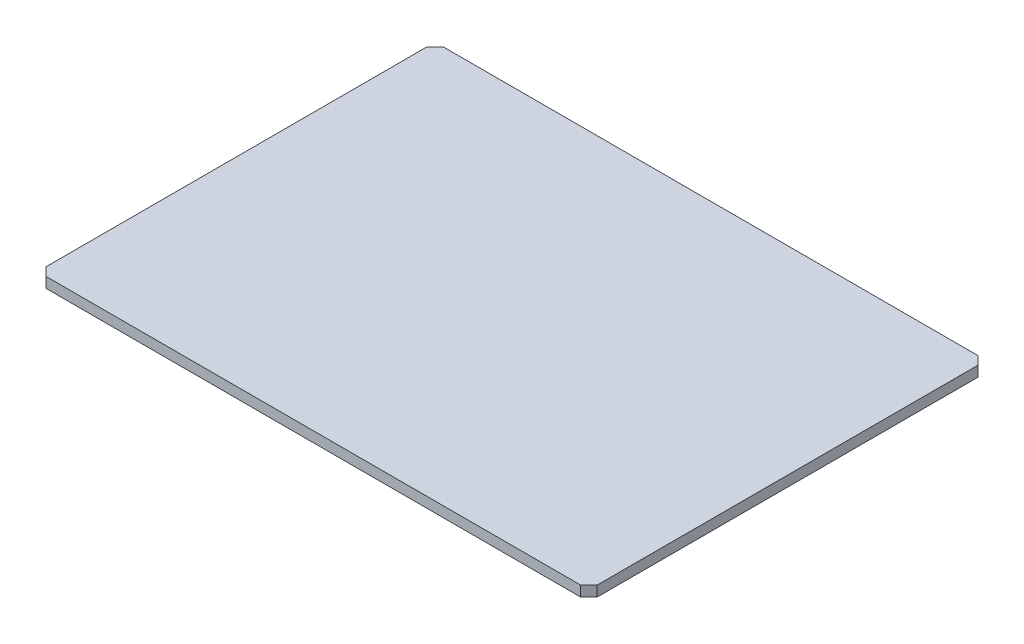
SolidWorks part; units mm, degrees
ref_plane "Front Plane" through (0, 0, 0) normal (0, 0, 1) x (1, 0, 0)
ref_plane "Top Plane" through (0, 0, 0) normal (0, 1, 0) x (1, 0, 0)
ref_plane "Right Plane" through (0, 0, 0) normal (1, 0, 0) x (0, 0, -1)
sketch "Sketch2" plane through (0, 0, 0) normal (0, 1, 0) x (1, 0, 0)
  line L1 (-66.3, 47.8) -> (66.3, 47.8)
  line L2 (-66.3, 47.8) -> (-66.3, -47.8)
  line L3 (-66.3, -47.8) -> (66.3, -47.8)
  line L4 (66.3, 47.8) -> (66.3, -47.8)
  line L5 (-66.3, 47.8) -> (66.3, -47.8) construction
  line L6 (-66.3, -47.8) -> (66.3, 47.8) construction
  point P0 (0, 0)
  dimension "D1" = 132.6
  dimension "D2" = 95.6
extrude "Boss-Extrude1" add sketch "Sketch2" along normal blind 2.5
chamfer "Chamfer1" distance 2 angle 45 4 edges at (66.3, 1.25, 47.8) (-66.3, 1.25, 47.8) (66.3, 1.25, -47.8) (-66.3, 1.25, -47.8)
sketch "Sketch3" plane through (0, 0, 0) normal (0, -1, 0) x (1, 0, 0)
  line L0 (-58.425, 18.925) -> (-66.3, 18.925)
  line L1 (-66.3, -45.8) -> (-66.3, 45.8) construction
  line L2 (-66.3, 18.925) -> (-66.3, 8.675)
  line L3 (-66.3, 8.675) -> (-58.425, 8.675)
  line L4 (-64.3, 47.8) -> (64.3, 47.8) construction
  arc A0 (-58.425, 18.925) -> (-58.425, 8.675) centre (-58.425, 13.8) cw
  point P9 (-53.3, 13.8)
  dimension "D1" = 10.25
  dimension "D2" = 34
  dimension "D3" = 13
extrude "Boss-Extrude2" add sketch "Sketch3" along normal blind 1.3
